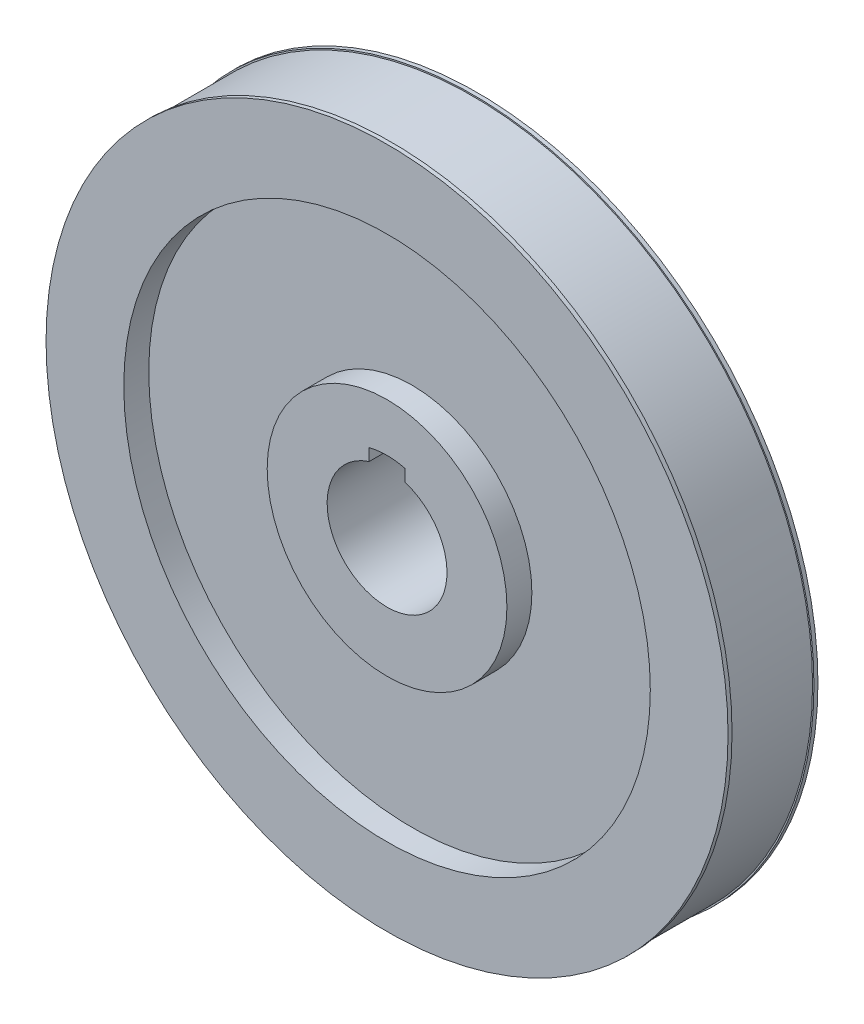
SolidWorks part; units mm, degrees
ref_plane "Front Plane" through (0, 0, 0) normal (0, 0, 1) x (1, 0, 0)
ref_plane "Top Plane" through (0, 0, 0) normal (0, 1, 0) x (1, 0, 0)
ref_plane "Right Plane" through (0, 0, 0) normal (1, 0, 0) x (0, 0, -1)
sketch "Sketch1" plane through (0, 0, 0) normal (0, 0, 1) x (1, 0, 0)
  circle A0 centre (0, 0) radius 170
  dimension "D1" = 340
extrude "Boss-Extrude1" add sketch "Sketch1" along normal mid plane 45
sketch "Sketch2" plane through (0, 0, 22.5) normal (0, 0, 1) x (1, 0, 0)
  circle A2 centre (0, 0) radius 170.69
  circle A3 centre (0, 0) radius 170.69
  dimension "D1" = 0.69
extrude "Boss-Extrude2" add sketch "Sketch2" against normal blind 2
mirror "Mirror1" about plane through (0, 0, 0) normal (0, 0, 1) of "Boss-Extrude2"
sketch "Sketch5" plane through (0, 0, 0) normal (0, 0, 1) x (1, 0, 0)
  circle A0 centre (0, 0) radius 131.78
  circle A1 centre (0, 0) radius 60
  circle A2 centre (0, 0) radius 170.69 construction
  dimension "D1" = 120
  dimension "D2" = 38.91
extrude "Cut-Extrude3" cut sketch "Sketch5" along normal through all from offset 10
mirror "Mirror2" about plane through (0, 0, 0) normal (0, 0, 1) of "Cut-Extrude3"
sketch "Sketch6" plane through (0, 0, 22.5) normal (0, 0, 1) x (1, 0, 0)
  circle A0 centre (0, 0) radius 30
  dimension "D1" = 60
extrude "Cut-Extrude4" cut sketch "Sketch6" against normal through all
sketch "Sketch7" plane through (0, 0, 22.5) normal (0, 0, 1) x (1, 0, 0)
  line L0 (0, 0) -> (0, 70.7854) construction
  line L1 (9, 20.2729) -> (9, 34.6503)
  line L2 (-9, 20.2729) -> (-9, 34.6503)
  line L3 (-9, 20.2729) -> (9, 20.2729)
  line L4 (-9, 0) -> (-9, 70.7854) construction
  line L5 (9, 0) -> (9, 70.7854) construction
  circle A2 centre (0, 0) radius 35.8
  arc A3 (9, 34.6503) -> (-9, 34.6503) centre (0, 0) ccw
  dimension "D4" = 20.2729
  dimension "D1" = 9
  dimension "D2" = 9
  dimension "D3" = 5.8
extrude "Cut-Extrude5" cut sketch "Sketch7" against normal through all
